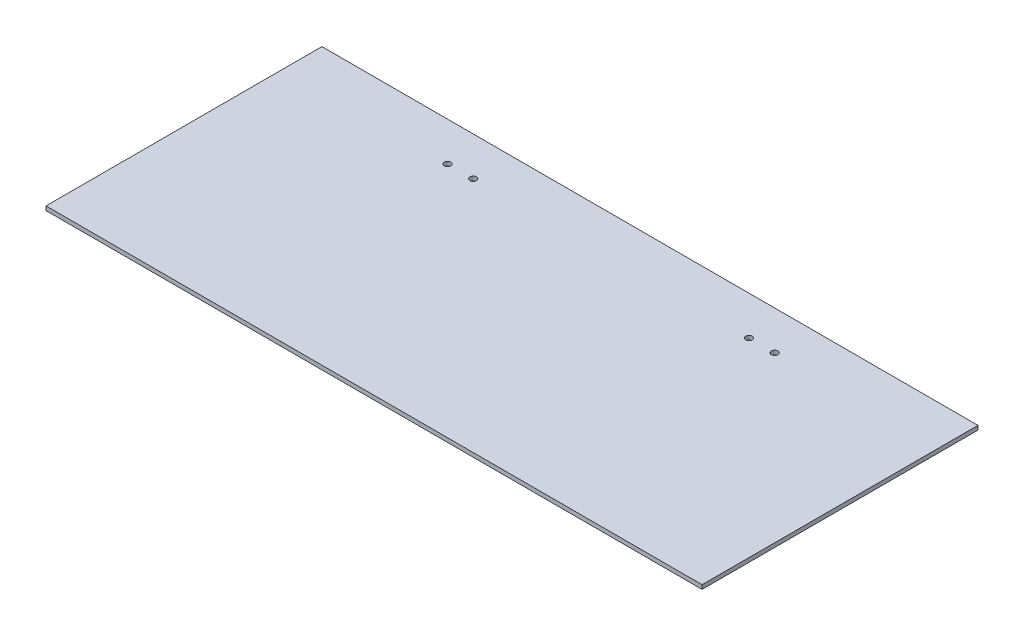
SolidWorks part; units mm, degrees
ref_plane "Front Plane" through (0, 0, 0) normal (0, 0, 1) x (1, 0, 0)
ref_plane "Top Plane" through (0, 0, 0) normal (0, 1, 0) x (1, 0, 0)
ref_plane "Right Plane" through (0, 0, 0) normal (1, 0, 0) x (0, 0, -1)
sketch "Sketch1" plane through (0, 0, 0) normal (0, 1, 0) x (1, 0, 0)
  line L0 (-254.7938, -107.1562) -> (254.7938, -107.1562)
  line L1 (-254.7938, -107.1562) -> (-254.7938, 107.1563)
  line L2 (254.7938, -107.1562) -> (254.7937, 107.1563)
  line L3 (-254.7938, 107.1563) -> (254.7937, 107.1563)
  line L4 (-254.7938, -107.1562) -> (254.7937, 107.1563) construction
  line L5 (254.7938, -107.1562) -> (-254.7938, 107.1563) construction
  point P1 (0, 0)
  dimension "D1" = 509.5875
  dimension "D2" = 214.3125
extrude "Boss-Extrude1" add sketch "Sketch1" along normal blind 3.175
sketch "Sketch2" plane through (0, 3.175, 0) normal (0, 1, 0) x (1, 0, 0)
  line L0 (254.7937, 107.1563) -> (-254.7938, 107.1563) construction
  circle A0 centre (-127, 76.9938) radius 2.54
  circle A1 centre (-107.1563, 76.9938) radius 2.54
  circle A2 centre (107.1563, 76.9938) radius 2.54
  circle A3 centre (127, 76.9938) radius 2.54
  dimension "D1" = 5.08
  dimension "D2" = 5.08
  dimension "D3" = 5.08
  dimension "D4" = 5.08
  dimension "D5" = 19.8438
  dimension "D6" = 19.8438
  dimension "D7" = 30.1625
  dimension "D8" = 127
  dimension "D9" = 127
extrude "Cut-Extrude1" cut sketch "Sketch2" against normal blind 3.175
